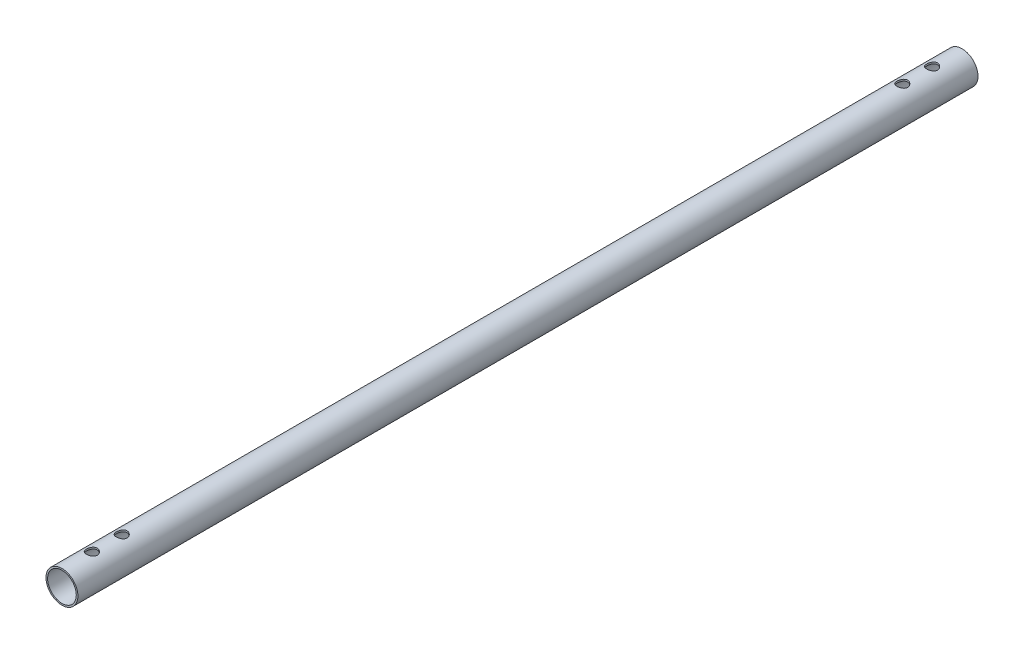
SolidWorks part; units mm, degrees
material "Galvanized Steel"
ref_plane "Front Plane" through (0, 0, 0) normal (0, 0, 1) x (1, 0, 0)
ref_plane "Top Plane" through (0, 0, 0) normal (0, 1, 0) x (1, 0, 0)
ref_plane "Right Plane" through (0, 0, 0) normal (1, 0, 0) x (0, 0, -1)
sketch "Sketch1" plane through (0, 0, 0) normal (0, 0, 1) x (1, 0, 0)
  circle A0 centre (0, 0) radius 13.35
  circle A1 centre (0, 0) radius 11.7
  dimension "D1" = 26.7
  dimension "D2" = 23.4
extrude "Boss-Extrude1" add sketch "Sketch1" along normal mid plane 753
sketch "Sketch2" plane through (0, 0, 0) normal (0, 1, 0) x (1, 0, 0)
  line L0 (-13.35, -376.5) -> (13.35, -376.5) construction
  line L1 (13.35, 376.5) -> (-13.35, 376.5) construction
  circle A0 centre (0, -351.5) radius 4.5
  circle A1 centre (0, -326.5) radius 4.5
  circle A2 centre (0, 351.5) radius 4.5
  circle A3 centre (0, 326.5) radius 4.5
  dimension "D1" = 9
  dimension "D2" = 25
  dimension "D3" = 25
  dimension "D4" = 25
  dimension "D5" = 25
  dimension "D6" = 9
  dimension "D7" = 9
extrude "Cut-Extrude1" cut sketch "Sketch2" against normal through all both and the other way through all
sketch "Sketch3" plane through (0, 0, -376.5) normal (0, 0, -1) x (-1, 0, 0)
  circle A0 centre (0, 0) radius 12
  dimension "D1" = 24
extrude "Cut-Extrude2" cut sketch "Sketch3" against normal blind 70
sketch "Sketch4" plane through (0, 0, 376.5) normal (0, 0, 1) x (1, 0, 0)
  circle A0 centre (0, 0) radius 12
  dimension "D1" = 24
extrude "Cut-Extrude3" cut sketch "Sketch4" against normal blind 70
